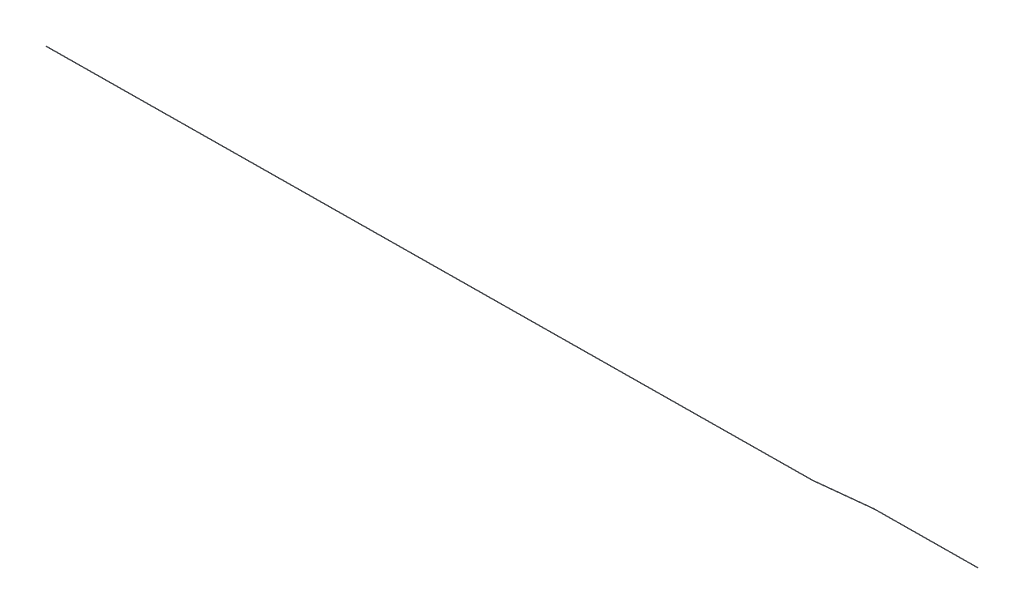
SolidWorks part; units mm, degrees
material "Nickel"
ref_plane "Front Plane" through (0, 0, 0) normal (0, 0, 1) x (1, 0, 0)
ref_plane "Top Plane" through (0, 0, 0) normal (0, 1, 0) x (1, 0, 0)
ref_plane "Right Plane" through (0, 0, 0) normal (1, 0, 0) x (0, 0, -1)
sketch3d "3DSketch1"
  line L0 (-387.1581, -7.565, -0.7916) -> (276.6329, -1.8533, -1.4099)
  line L1 (324.2539, -2.0644, -6.816) -> (276.6329, -1.8533, -1.4099)
  line L2 (324.2539, -2.0644, -6.816) -> (413.9248, -1.5856, -7.116)
sweep "Sweep1" add path "3DSketch1" circular profile diameter 0.3 parameters "D3"=0.3
